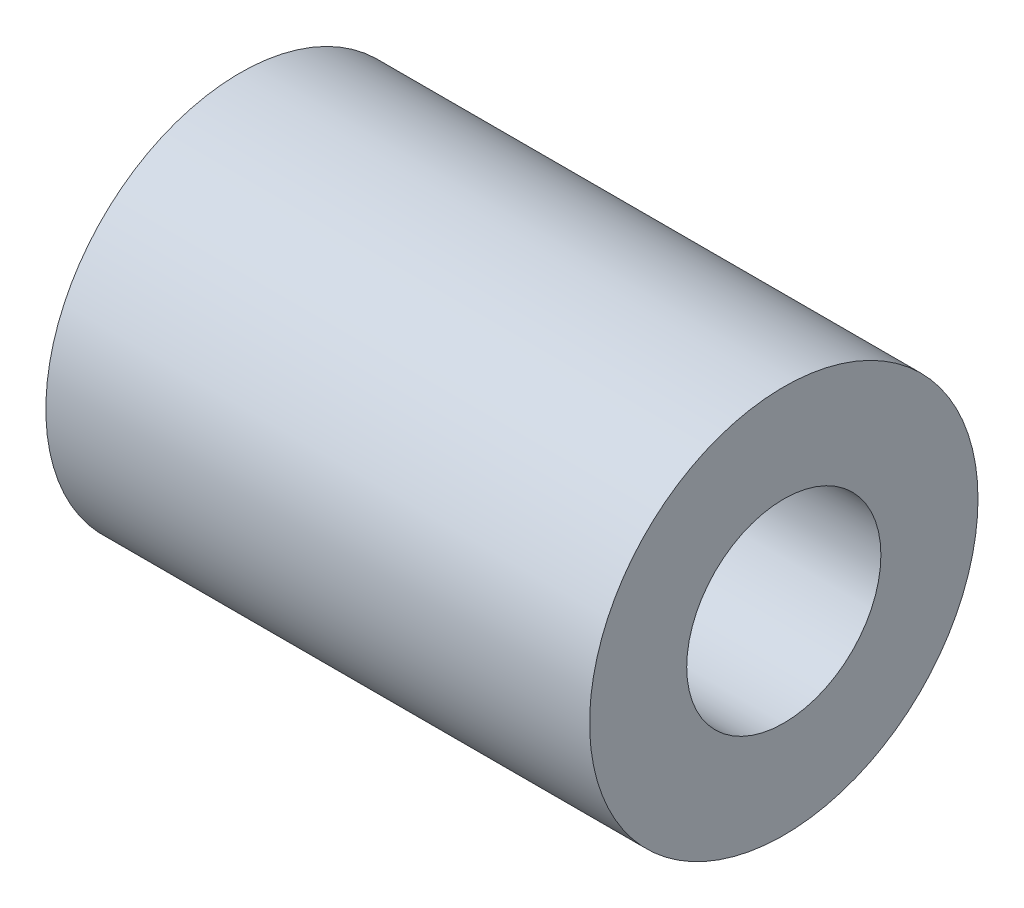
SolidWorks part; units mm, degrees
material "Nylon 101"
ref_plane "Front Plane" through (0, 0, 0) normal (0, 0, 1) x (1, 0, 0)
ref_plane "Top Plane" through (0, 0, 0) normal (0, 1, 0) x (1, 0, 0)
ref_plane "Right Plane" through (0, 0, 0) normal (1, 0, 0) x (0, 0, -1)
sketch "Sketch1" plane through (0, 0, 0) normal (1, 0, 0) x (0, 0, -1)
  circle A0 centre (0, 0) radius 2.5
  circle A1 centre (0, 0) radius 1.25
  dimension "D2" = 5
  dimension "D1" = 2.5
extrude "Boss-Extrude1" add sketch "Sketch1" along normal blind 7
